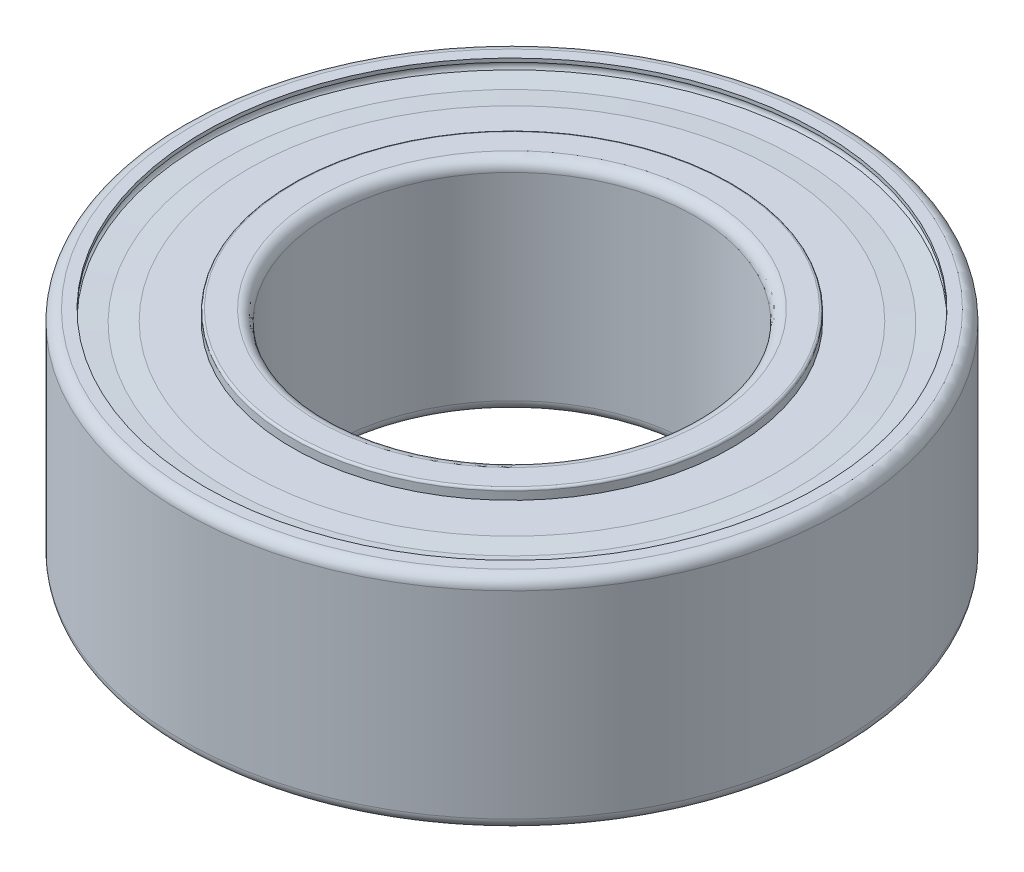
SolidWorks part; units mm, degrees
material "Nerezová ocel (feritická)"
ref_plane "Přední rovina" through (0, 0, 0) normal (0, 0, 1) x (1, 0, 0)
ref_plane "Horní rovina" through (0, 0, 0) normal (0, 1, 0) x (1, 0, 0)
ref_plane "Pravá rovina" through (0, 0, 0) normal (1, 0, 0) x (0, 0, -1)
sketch "Skica4" plane through (0, 0, 0) normal (0, 0, 1) x (1, 0, 0)
  line L0 (4.5, 1.35) -> (4.5, -1.35)
  line L1 (4.35, -1.5) -> (4.2, -1.5)
  line L2 (4.2, -1.5) -> (4.2, -1.45)
  line L3 (3.85, -1.2172) -> (4.2132, -1.271)
  line L4 (3.85, -1.2172) -> (3.85, -0.4472)
  line L5 (3.85, 0.4472) -> (3.85, 1.2172)
  line L6 (3.85, 1.2172) -> (4.2132, 1.271)
  line L7 (4.35, 1.5) -> (4.2, 1.5)
  line L8 (4.2, 1.5) -> (4.2, 1.45)
  line L9 (0, 0) -> (0, 18.4294) construction
  arc A0 (4.35, 1.5) -> (4.5, 1.35) centre (4.35, 1.35) cw
  arc A1 (4.35, -1.5) -> (4.5, -1.35) centre (4.35, -1.35) ccw
  arc A2 (4.2, 1.45) -> (4.2132, 1.271) centre (4.2, 1.36) cw
  arc A3 (3.85, 0.4472) -> (3.85, -0.4472) centre (3.45, 0) cw
  arc A4 (4.2, -1.45) -> (4.2132, -1.271) centre (4.2, -1.36) ccw
  point P26 (4.5, 0)
  point P29 (4.275, -1.5)
  dimension "D3" = 0.09
  dimension "D6" = 0.15
  dimension "D7" = 0.6
  dimension "D1" = 4.5
  dimension "D2" = 3.85
  dimension "D4" = 0.05
  dimension "D5" = 0.15
  dimension "D8" = 0.77
  dimension "D9" = 3
  dimension "D10" = 1.05
revolve "Rotovat2" add sketch "Skica4" angle 360 about L9
sketch "Skica5" plane through (0, 0, 0) normal (0, 0, 1) x (1, 0, 0)
  line L0 (2.5, 1.35) -> (2.5, -1.35)
  line L1 (2.65, 1.5) -> (2.97, 1.5)
  line L2 (3, 1.47) -> (3, 1.36)
  line L3 (3, 1.36) -> (3.6, 1.36)
  line L4 (3.6, 1.36) -> (3.9, 1.34)
  line L5 (3.9, 1.34) -> (4.2, 1.36)
  line L6 (4.2, 1.36) -> (4.2, 1.31)
  line L7 (4.2, 1.31) -> (3.9, 1.27)
  line L8 (3.9, 1.27) -> (3.6, 1.27)
  line L9 (3.6, 1.27) -> (3, 1.31)
  line L10 (3, 1.31) -> (3, 0.3969)
  line L11 (2.65, -1.5) -> (2.97, -1.5)
  line L12 (0, 0) -> (0, 20.363) construction
  line L13 (3, -1.47) -> (3, -1.36)
  line L21 (3, -1.31) -> (3, -0.3969)
  line L22 (3, -1.36) -> (3.6, -1.36)
  line L23 (3.6, -1.36) -> (3.8962, -1.3083)
  line L24 (3.8962, -1.3083) -> (4.1924, -1.36)
  line L25 (4.1924, -1.36) -> (4.1924, -1.31)
  line L26 (4.1924, -1.31) -> (3.8975, -1.2419)
  line L27 (3.8975, -1.2419) -> (3.5975, -1.2419)
  line L28 (3.5975, -1.2419) -> (3, -1.31)
  line L29 (-4.2, -1.5) -> (4.2, -1.5) construction
  arc A0 (2.65, -1.5) -> (2.5, -1.35) centre (2.65, -1.35) cw
  arc A1 (2.65, 1.5) -> (2.5, 1.35) centre (2.65, 1.35) ccw
  arc A2 (3, 1.47) -> (2.97, 1.5) centre (2.97, 1.47) ccw
  arc A3 (3, -1.47) -> (2.97, -1.5) centre (2.97, -1.47) cw
  arc A4 (3, 0.3969) -> (3, -0.3969) centre (3.45, 0) ccw
  dimension "D3" = 0.15
  dimension "D4" = 0.11
  dimension "D5" = 0.03
  dimension "D7" = 0.6
  dimension "D1" = 2.5
  dimension "D2" = 3
  dimension "D6" = 0.6
  dimension "D8" = 0.95
  dimension "D9" = 3
  dimension "D10" = 1.2
  dimension "D11" = 0.3
  dimension "D12" = 0.05
  dimension "D13" = 0.9
  dimension "D14" = 0.6
  dimension "D15" = 0.09
  dimension "D16" = 0.05
  dimension "D17" = 0.05
revolve "Rotovat3" add sketch "Skica5" angle 360 about L12
sketch "Skica6" plane through (0, 0, 0) normal (0, 0, 1) x (1, 0, 0)
  line L0 (3.45, 0.6) -> (3.45, -0.6)
  line L4 (-4.2, -1.5) -> (4.2, -1.5) construction
  arc A0 (3.45, 0.6) -> (3.45, -0.6) centre (3.45, 0) cw
  dimension "D1" = 0.6
  dimension "D2" = 1.5
  dimension "D3" = 3.45
revolve "Rotovat4" add sketch "Skica6" angle 360 about L0
pattern_circular "Kruhové pole1" count 8 over 360 about axis through (0, 0, 0) along (0, 1, 0) of bodies 105
